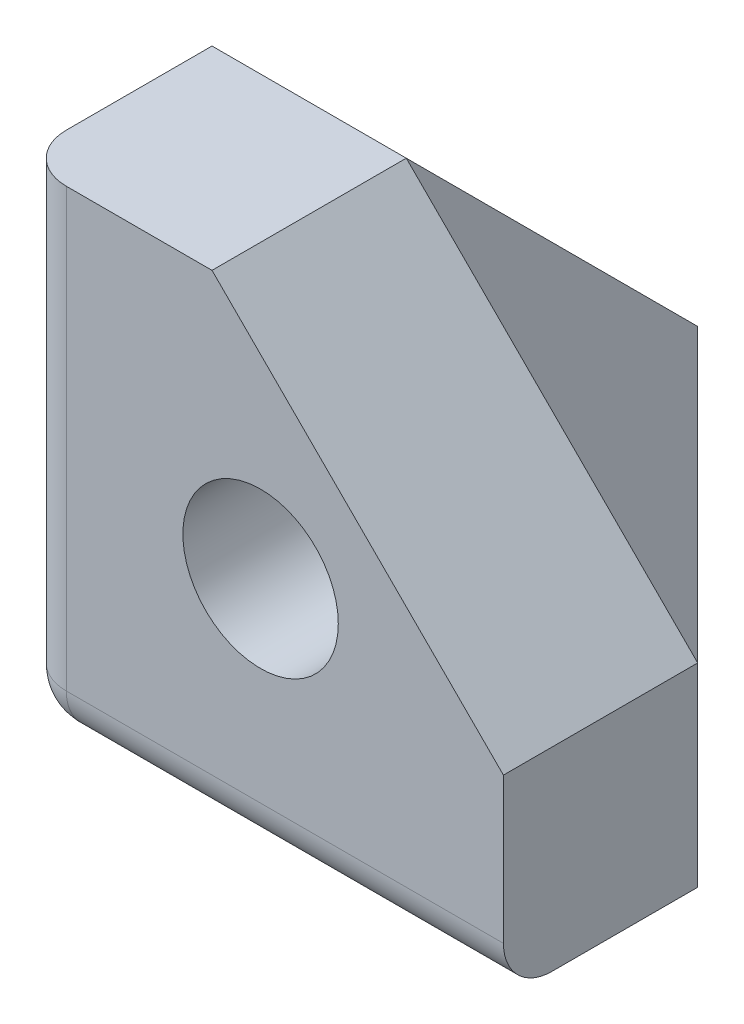
SolidWorks part; units mm, degrees
ref_plane "Front Plane" through (0, 0, 0) normal (0, 0, 1) x (1, 0, 0)
ref_plane "Top Plane" through (0, 0, 0) normal (0, 1, 0) x (1, 0, 0)
ref_plane "Right Plane" through (0, 0, 0) normal (1, 0, 0) x (0, 0, -1)
sketch "Sketch1" plane through (0, 0, 0) normal (0, 1, 0) x (1, 0, 0)
  line L1 (-5, -5) -> (5, -5)
  line L2 (-5, -5) -> (-5, 5)
  line L3 (-5, 5) -> (5, 5)
  line L4 (5, -5) -> (5, 5)
  line L5 (-5, -5) -> (5, 5) construction
  line L6 (-5, 5) -> (5, -5) construction
  point P0 (0, 0)
  dimension "D1" = 10
extrude "Boss-Extrude1" add sketch "Sketch1" along normal blind 10
sketch "Sketch2" plane through (0, 0, 5) normal (0, 0, 1) x (1, 0, 0)
  line L0 (-5, 10) -> (5, 0) construction
  circle A0 centre (0, 5) radius 1.6
  dimension "D1" = 3.2
extrude "Cut-Extrude1" cut sketch "Sketch2" against normal blind 3.2
sketch "Sketch3" plane through (0, 0, 0) normal (0, -1, 0) x (-1, 0, 0)
  line L0 (5, -5) -> (-5, 5) construction
  circle A0 centre (0, 0) radius 1.6
  dimension "D1" = 3.2
extrude "Cut-Extrude3" cut sketch "Sketch3" against normal blind 3.2
sketch "Sketch4" plane through (-5, 0, 0) normal (1, 0, 0) x (0, 0, -1)
  line L0 (5, 10) -> (-5, 0) construction
  circle A0 centre (0, 5) radius 1.6
  dimension "D1" = 3.2
extrude "Cut-Extrude4" cut sketch "Sketch4" along normal blind 3.2
fillet "Fillet2" radius 1 3 edges at (-5, 0, 0) (-5, 5, 5) (0, 0, 5)
chamfer "Chamfer1" distance 6 angle 45 3 edges at (5, 5, -5) (5, 10, 0) (0, 10, -5)
